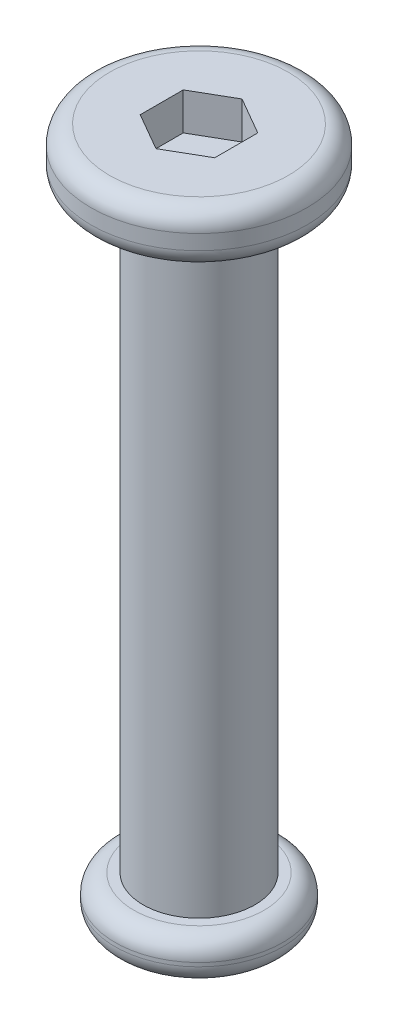
SolidWorks part; units mm, degrees
material "AISI 304"
ref_plane "前视基准面" through (0, 0, 0) normal (0, 0, 1) x (1, 0, 0)
ref_plane "上视基准面" through (0, 0, 0) normal (0, 1, 0) x (1, 0, 0)
ref_plane "右视基准面" through (0, 0, 0) normal (1, 0, 0) x (0, 0, -1)
other "Configuration Table"
sketch "草图1" plane through (0, 0, 0) normal (0, 1, 0) x (1, 0, 0)
  circle A0 centre (0, 0) radius 2.9
  dimension "D1" = 5.8
extrude "凸台-拉伸1" add sketch "草图1" along normal blind 1.4
sketch "草图2" plane through (0, 1.4, 0) normal (0, 1, 0) x (1, 0, 0)
  line L0 (0, 0) -> (0, 3.5021) construction
  line L1 (1, 0.5774) -> (0, 1.1547)
  line L2 (0, 1.1547) -> (-1, 0.5774)
  line L3 (-1, 0.5774) -> (-1, -0.5774)
  line L4 (-1, -0.5774) -> (0, -1.1547)
  line L5 (0, -1.1547) -> (1, -0.5774)
  line L6 (1, -0.5774) -> (1, 0.5774)
  circle A0 centre (0, 0) radius 1 construction
  point P1 (0, 1.1547)
  dimension "D1" = 2
extrude "切除-拉伸1" cut sketch "草图2" against normal blind 1
sketch "草图3" plane through (0, 0, 0) normal (0, -1, 0) x (1, 0, 0)
  circle A0 centre (0, 0) radius 1.5
  dimension "D1" = 3
extrude "凸台-拉伸2" add sketch "草图3" along normal blind 16
sketch "草图4" plane through (0, -16, 0) normal (0, -1, 0) x (1, 0, 0)
  circle A0 centre (0, 0) radius 2.25
  dimension "D1" = 4.5
extrude "凸台-拉伸3" add sketch "草图4" along normal blind 1.1
sketch "草图5" plane through (0, -17.1, 0) normal (0, -1, 0) x (1, 0, 0)
  line L0 (0, 0) -> (0, 2.5586) construction
  line L1 (0.65, 0.3753) -> (0, 0.7506)
  line L2 (0, 0.7506) -> (-0.65, 0.3753)
  line L3 (-0.65, 0.3753) -> (-0.65, -0.3753)
  line L4 (-0.65, -0.3753) -> (0, -0.7506)
  line L5 (0, -0.7506) -> (0.65, -0.3753)
  line L6 (0.65, -0.3753) -> (0.65, 0.3753)
  circle A0 centre (0, 0) radius 0.65 construction
  point P1 (0, 0.7506)
  dimension "D1" = 1.3
extrude "切除-拉伸2" cut sketch "草图5" against normal blind 0.8
fillet "圆角1" radius 0.5 4 edges at (0, 1.4, 2.9) (0, 0, 2.9) (0, -16, -2.25) (0, -17.1, -2.25)
